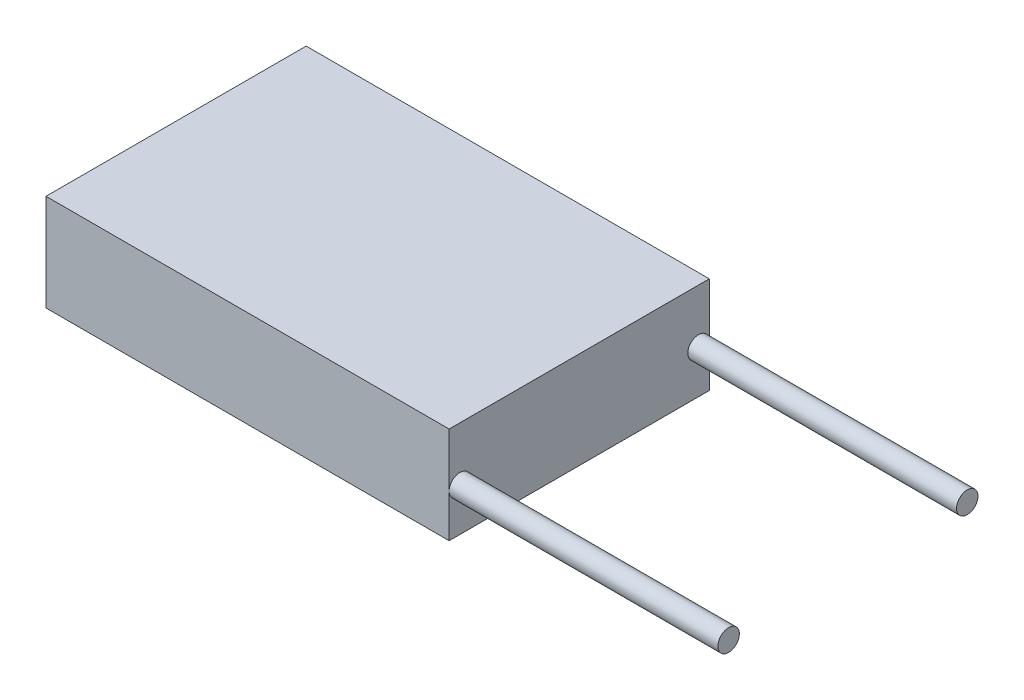
SolidWorks part; units mm, degrees
ref_plane "Front Plane" through (0, 0, 0) normal (0, 0, 1) x (1, 0, 0)
ref_plane "Top Plane" through (0, 0, 0) normal (0, 1, 0) x (1, 0, 0)
ref_plane "Right Plane" through (0, 0, 0) normal (1, 0, 0) x (0, 0, -1)
sketch "Sketch2" plane through (0, 0, 0) normal (0, 1, 0) x (1, 0, 0)
  line L1 (-18.75, 12.1) -> (18.75, 12.1)
  line L2 (-18.75, 12.1) -> (-18.75, -12.1)
  line L3 (-18.75, -12.1) -> (18.75, -12.1)
  line L4 (18.75, 12.1) -> (18.75, -12.1)
  line L5 (-18.75, 12.1) -> (18.75, -12.1) construction
  line L6 (-18.75, -12.1) -> (18.75, 12.1) construction
  point P0 (0, 0)
  dimension "D1" = 37.5
  dimension "D2" = 24.2
extrude "Boss-Extrude1" add sketch "Sketch2" along normal blind 9
sketch "Sketch3" plane through (18.75, 0, 0) normal (1, 0, 0) x (0, 0, -1)
  line L2 (-12.1, 9) -> (-12.1, 0) construction
  line L3 (-12.1, 0) -> (12.1, 0) construction
  circle A0 centre (-11.1, 4) radius 1
  dimension "D1" = 2
  dimension "D2" = 4
extrude "Boss-Extrude2" add sketch "Sketch3" along normal blind 25
mirror "Mirror1" about plane through (0, 0, 0) normal (0, 0, 1) of "Boss-Extrude2"
